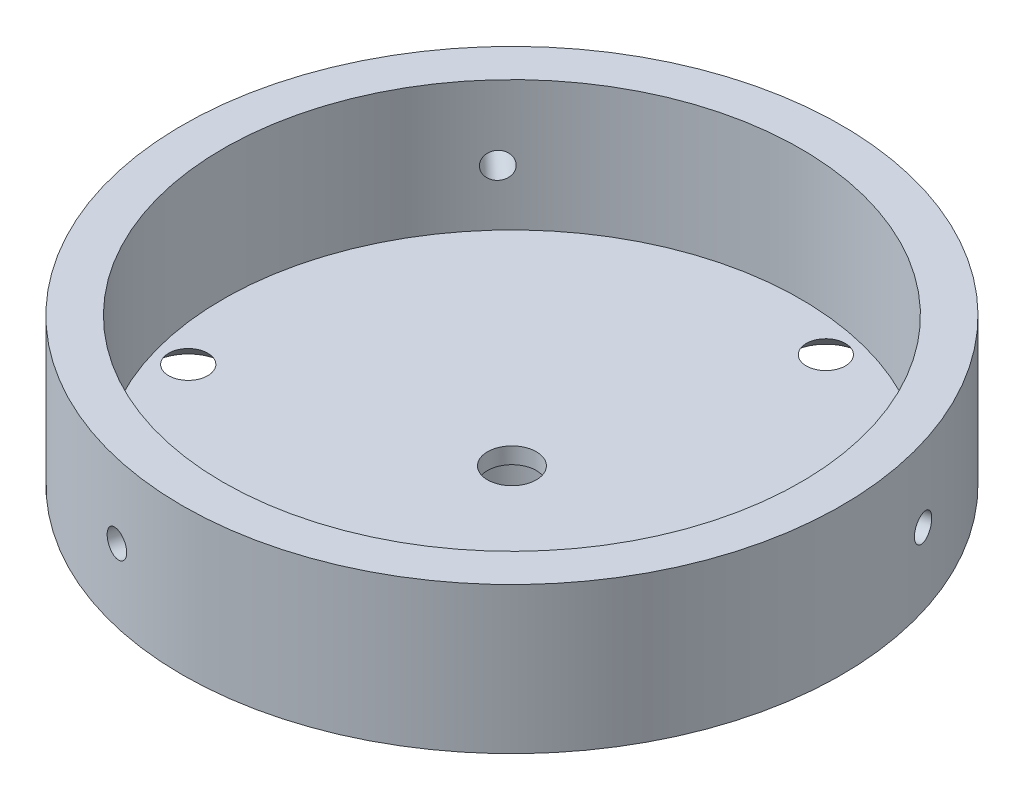
SolidWorks part; units mm, degrees
ref_plane "Front Plane" through (0, 0, 0) normal (0, 0, 1) x (1, 0, 0)
ref_plane "Top Plane" through (0, 0, 0) normal (0, 1, 0) x (1, 0, 0)
ref_plane "Right Plane" through (0, 0, 0) normal (1, 0, 0) x (0, 0, -1)
sketch "Sketch1" plane through (0, 0, 0) normal (0, 1, 0) x (1, 0, 0)
  circle A0 centre (0, 0) radius 20.25
  dimension "D1" = 40.5
extrude "Boss-Extrude1" add sketch "Sketch1" along normal blind 9
sketch "Sketch2" plane through (0, 9, 0) normal (0, 1, 0) x (1, 0, 0)
  circle A0 centre (0, 0) radius 17.75
  dimension "D1" = 35.5
extrude "Cut-Extrude1" cut sketch "Sketch2" against normal blind 8
hole_wizard "CSK SLOT for M2 Countersunk Flat Head Screw1" positions "Sketch3" profile "Sketch4" size "M2" standard "ISO" slot yes
sketch "Sketch3" plane through (0, 0, 0) normal (0, -1, 0) x (-1, 0, 0)
  line L0 (-11.6097, -11.0097) -> (0, 0)
  point P0 (-11.6097, -11.0097)
  dimension "D1" = 16
sketch "Sketch4" plane through (11.6097, 0, 11.0097) normal (1, 0, 0) x (0, 0, -1)
  line L0 (0, 0) -> (0, 6.521)
  line L1 (0, 6.521) -> (1.2, 5.8)
  line L2 (1.2, 5.8) -> (1.2, 1)
  line L3 (1.2, 1) -> (2.2, 0)
  line L5 (2.2, 0) -> (0, 0)
  line L6 (-1.2, 1) -> (-2.2, 0) construction
  line L10 (0, 6.521) -> (-1.2, 5.8) construction
  line L11 (0, -6.35) -> (0, 107.95) construction
  dimension "Hole Dia." = 2.4
  dimension "Hole Depth" = 5.8
  dimension "Near C'Sink Dia." = 4.4
  dimension "Near C'Sink Angle" = 90
  dimension "Drill Angle" = 118
pattern_circular "CirPattern1" count 3 over 360 about axis through (0, 0, 0) along (0, 1, 0) of "CSK SLOT for M2 Countersunk Flat Head Screw1"
sketch "Sketch5" plane through (0, 0, 0) normal (0, -1, 0) x (1, 0, 0)
  circle A0 centre (0, 0) radius 1.5
  dimension "D1" = 3
extrude "Cut-Extrude2" cut sketch "Sketch5" against normal blind 8
hole_wizard "M2 Tapped Hole1" positions "3DSketch1" profile "Sketch6" tap size "M2" standard "ISO"
sketch3d "3DSketch1"
  point P0 (-4.5608, 4.4458, 19.7297)
sketch "Sketch6" plane through (-4.5608, 4.4458, 19.7297) normal (0, 1, 0) x (0.9743, 0, 0.2252)
  line L0 (0, 0) -> (0, 4.9807)
  line L1 (0, 4.9807) -> (0.8, 4.5)
  line L2 (0.8, 4.5) -> (0.8, 0)
  line L5 (0.8, 0) -> (0, 0)
  line L10 (0, 4.9807) -> (-0.8, 4.5) construction
  line L11 (0, -6.35) -> (0, 107.95) construction
  dimension "Tap Drill Dia." = 1.6
  dimension "Tap Drill Depth" = 4.5
  dimension "Drill Angle" = 118
pattern_circular "CirPattern2" count 3 over 360 about axis through (0, 9, 0) along (0, -1, 0) of "M2 Tapped Hole1"
sketch "Sketch7" plane through (0, 0, 0) normal (0, -1, 0) x (1, 0, 0)
  circle A0 centre (0, 0) radius 4.5
  dimension "D1" = 9
extrude "Boss-Extrude3" add sketch "Sketch7" along normal blind 4
sketch "Sketch8" plane through (0, -4, 0) normal (0, -1, 0) x (1, 0, 0)
  circle A0 centre (0, 0) radius 3.265
  dimension "D1" = 6.53
extrude "Cut-Extrude3" cut sketch "Sketch8" against normal blind 4
